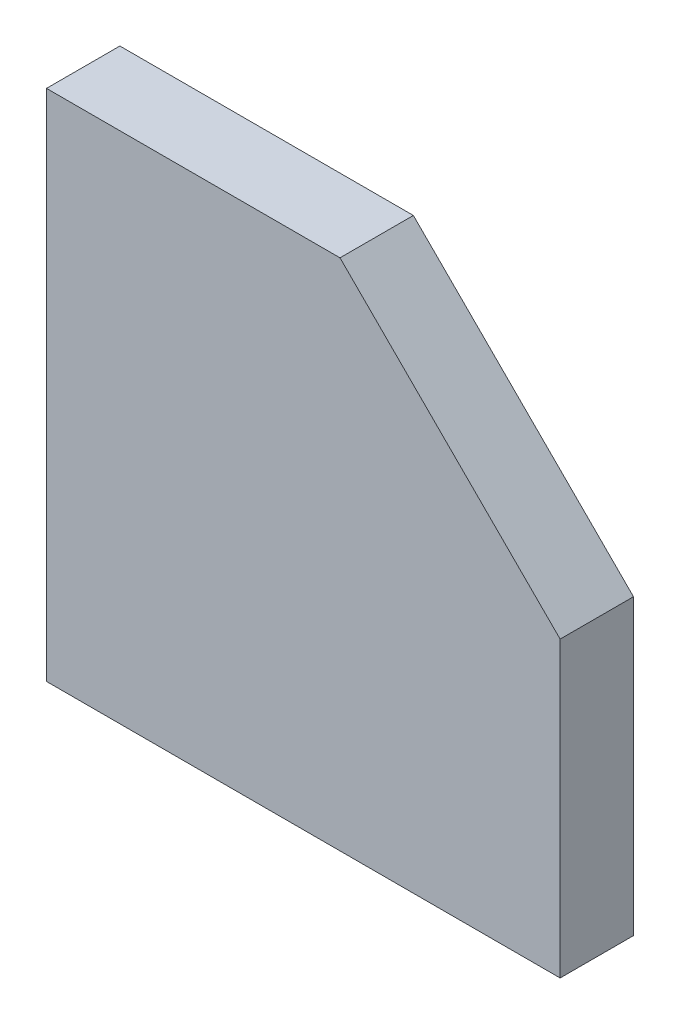
SolidWorks part; units mm, degrees
material "Д16Т ГОСТ 4784-74"
ref_plane "Спереди" through (0, 0, 0) normal (0, 0, 1) x (1, 0, 0)
ref_plane "Сверху" through (0, 0, 0) normal (0, 1, 0) x (1, 0, 0)
ref_plane "Справа" through (0, 0, 0) normal (1, 0, 0) x (0, 0, -1)
sketch "Эскиз1" plane through (0, 0, 0) normal (0, 0, 1) x (1, 0, 0)
  line L0 (40, 70) -> (70, 40)
  line L1 (0, 0) -> (70, 0)
  line L2 (0, 0) -> (0, 70)
  line L3 (0, 70) -> (40, 70)
  line L4 (70, 0) -> (70, 40)
  point P1 (70, 70)
  dimension "D1" = 70
  dimension "D2" = 70
extrude "Бобышка-Вытянуть1" add sketch "Эскиз1" along normal blind 10
